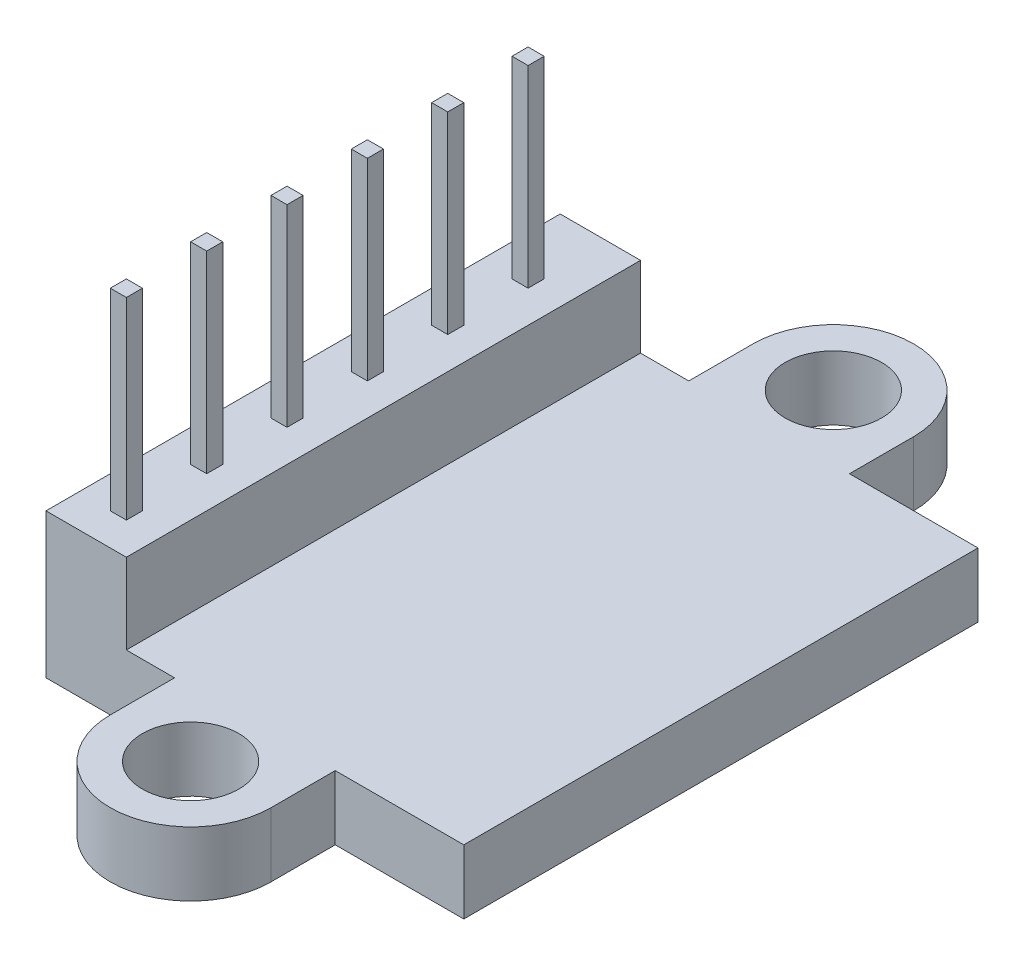
SolidWorks part; units mm, degrees
material "CA"
ref_plane "Front Plane" through (0, 0, 0) normal (0, 0, 1) x (1, 0, 0)
ref_plane "Top Plane" through (0, 0, 0) normal (0, 1, 0) x (1, 0, 0)
ref_plane "Right Plane" through (0, 0, 0) normal (1, 0, 0) x (0, 0, -1)
sketch "Sketch1" plane through (0, 0, 0) normal (0, 1, 0) x (1, 0, 0)
  line L0 (-6.5, 0) -> (6.5, 0) construction
  line L1 (-6.5, -8) -> (-2.5, -8)
  line L2 (-6.5, -8) -> (-6.5, 8)
  line L3 (-6.5, 8) -> (-2.5, 8)
  line L4 (6.5, -8) -> (6.5, 8)
  line L5 (-6.5, -8) -> (6.5, 8) construction
  line L6 (-6.5, 8) -> (6.5, -8) construction
  line L7 (0, 14.1285) -> (0, 8.5) construction
  line L8 (-2.5, 10) -> (-2.5, 8)
  line L9 (2.5, 10) -> (2.5, 8)
  line L10 (0, 0) -> (0, -16.566) construction
  line L11 (2.5, 8) -> (6.5, 8)
  line L12 (2.5, -10) -> (2.5, -8)
  line L13 (-2.5, -10) -> (-2.5, -8)
  line L14 (2.5, -8) -> (6.5, -8)
  circle A0 centre (0, 10) radius 1.5
  arc A1 (2.5, 10) -> (-2.5, 10) centre (0, 10) ccw
  circle A2 centre (0, 10) radius 2.5 construction
  circle A3 centre (0, -10) radius 1.5
  arc A4 (2.5, -10) -> (-2.5, -10) centre (0, -10) cw
  point P0 (0, 0)
  dimension "D3" = 3
  dimension "D4" = 20
  dimension "D1" = 13
  dimension "D2" = 16
  dimension "D5" = 1
extrude "Boss-Extrude1" add sketch "Sketch1" along normal blind 2
sketch "Sketch2" plane through (0, 2, 0) normal (0, 1, 0) x (1, 0, 0)
  line L0 (-6.5, -8) -> (-2.5, -8) construction
  line L1 (-6.5, 8) -> (-4, 8)
  line L2 (-6.5, 8) -> (-6.5, -8)
  line L3 (-6.5, -8) -> (-4, -8)
  line L4 (-4, 8) -> (-4, -8)
  line L5 (-6.5, 0) -> (-4, 0)
  line L6 (-6.5, -3) -> (-4, -3)
  line L15 (-6.5, -5.5) -> (-4, -5.5)
  line L16 (-6.5, 3) -> (-4, 3)
  line L17 (-6.5, 5.5) -> (-4, 5.5)
  line M20 (-2.5, 8) -> (-6.5, 8)
  line M21 (-6.5, 8) -> (-6.5, -8)
  line M22 (-6.5, -8) -> (-2.5, -8)
  dimension "D1" = 2.5
  dimension "D2" = 2.5
  dimension "D3" = 2.5
  dimension "D4" = 3
extrude "Boss-Extrude2" add sketch "Sketch2" along normal blind 2.5 contours L15 L2 L4 M22 | L15 L4 L6 M21 | L2 L6 L4 L5 | L16 L2 L5 L4 | L17 L2 L16 L4 | L17 L4 M21 M20
sketch "Sketch3" plane through (0, 4.5, 0) normal (0, 1, 0) x (1, 0, 0)
  line L0 (-6.5, 8) -> (-6.5, -8) construction
  line L1 (-5.5, -7) -> (-5, -7)
  line L2 (-5.5, -7) -> (-5.5, -6.5)
  line L3 (-5.5, -6.5) -> (-5, -6.5)
  line L4 (-5, -7) -> (-5, -6.5)
  line L5 (-5.5, -7) -> (-5, -6.5) construction
  line L6 (-5.5, -6.5) -> (-5, -7) construction
  line L7 (-6.5, -8) -> (-4, -8) construction
  line L8 (-5.5, -4.5) -> (-5.5, -4)
  line L9 (-5.5, -4.5) -> (-5, -4.5)
  line L10 (-5, -4.5) -> (-5, -4)
  line L11 (-5.5, -4) -> (-5, -4)
  line L12 (-5.5, -2) -> (-5.5, -1.5)
  line L13 (-5.5, -2) -> (-5, -2)
  line L14 (-5, -2) -> (-5, -1.5)
  line L15 (-5.5, -1.5) -> (-5, -1.5)
  line L16 (-5.5, 0.5) -> (-5.5, 1)
  line L17 (-5.5, 0.5) -> (-5, 0.5)
  line L18 (-5, 0.5) -> (-5, 1)
  line L19 (-5.5, 1) -> (-5, 1)
  line L20 (-5.5, 3) -> (-5.5, 3.5)
  line L21 (-5.5, 3) -> (-5, 3)
  line L22 (-5, 3) -> (-5, 3.5)
  line L23 (-5.5, 3.5) -> (-5, 3.5)
  line L24 (-5.5, 5.5) -> (-5.5, 6)
  line L25 (-5.5, 5.5) -> (-5, 5.5)
  line L26 (-5, 5.5) -> (-5, 6)
  line L27 (-5.5, 6) -> (-5, 6)
  point P0 (-5.25, -6.75)
  dimension "D1" = 1.25
  dimension "D2" = 1.25
  dimension "D3" = 0.5
  dimension "D4" = 0.5
  dimension "D5" = 0.5
  dimension "D6" = 6
extrude "Boss-Extrude3" add sketch "Sketch3" along normal blind 6 contours L8 L11 L10 L9 | L2 L1 L4 L3 | L12 L15 L14 L13 | L16 L19 L18 L17 | L20 L23 L22 L21 | L24 L27 L26 L25
sketch "Sketch4" plane through (0, 0, 0) normal (0, -1, 0) x (1, 0, 0)
  line L0 (6.5, 0) -> (-6.5, 0) construction
  line L1 (6.5, 8) -> (6.5, -8) construction
  line L2 (-6.5, -8) -> (-6.5, 8) construction
  line L4 (0.5, -2) -> (2.5, -2)
  line L5 (0.5, -2) -> (0.5, 2)
  line L6 (0.5, 2) -> (2.5, 2)
  line L7 (2.5, -2) -> (2.5, 2)
  line L8 (0.5, -2) -> (2.5, 2) construction
  line L9 (0.5, 2) -> (2.5, -2) construction
  point P6 (1.5, 0)
  dimension "D1" = 5
  dimension "D2" = 2
  dimension "D3" = 4
extrude "Boss-Extrude4" add sketch "Sketch4" along normal blind 1.5
